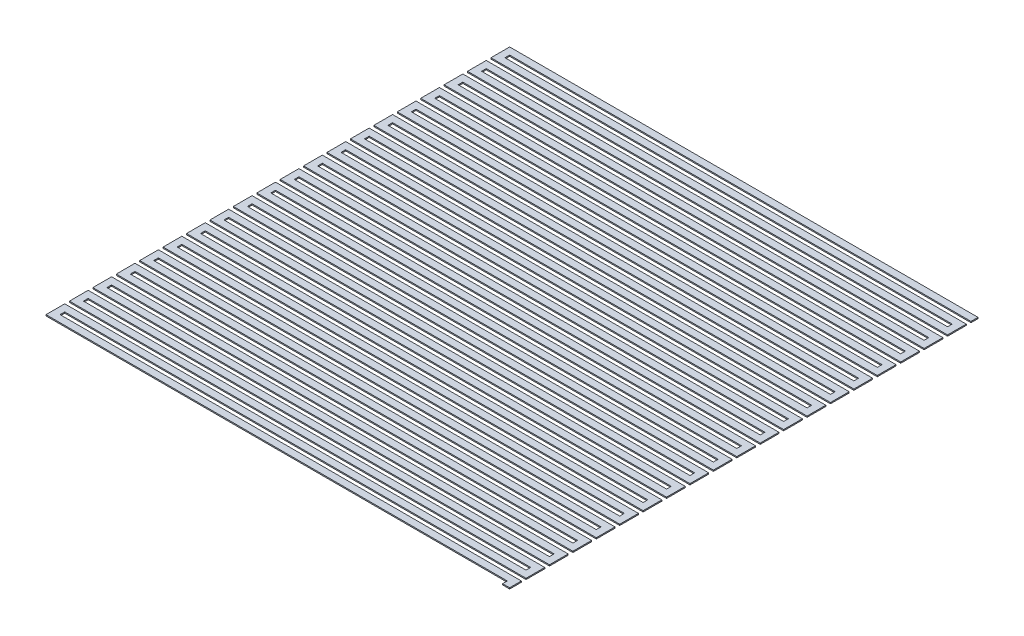
SolidWorks part; units mm, degrees
ref_plane "Front Plane" through (0, 0, 0) normal (0, 0, 1) x (1, 0, 0)
ref_plane "Top Plane" through (0, 0, 0) normal (0, 1, 0) x (1, 0, 0)
ref_plane "Right Plane" through (0, 0, 0) normal (1, 0, 0) x (0, 0, -1)
sketch "Base Guidlines" plane through (0, 0, 0) normal (0, 1, 0) x (1, 0, 0)
  line L0 (-4.5961, 9.2) -> (-4.5961, 8.5)
  line L1 (-10, -10) -> (10, -10)
  line L2 (-10, -10) -> (-10, 10)
  line L3 (-10, 10) -> (10, 10)
  line L4 (10, -10) -> (10, 10)
  line L5 (-10, -10) -> (10, 10) construction
  line L6 (-10, 10) -> (10, -10) construction
  line L7 (-10, 10) -> (10, 10)
  line L8 (-10, 10) -> (-10, 9.2)
  line L9 (-10, 9.2) -> (10, 9.2)
  line L10 (10, 10) -> (10, 9.2)
  line L11 (-4.5961, -9.2) -> (-4.5961, -8.5)
  line L12 (-10, -10) -> (10, -10)
  line L13 (-10, -10) -> (-10, -9.2)
  line L14 (-10, -9.2) -> (10, -9.2)
  line L15 (10, -10) -> (10, -9.2)
  line L17 (-10, -9.2) -> (10, -9.2)
  line L18 (-10, -9.2) -> (-10, -8.5)
  line L19 (-10, -8.5) -> (10, -8.5)
  line L20 (10, -9.2) -> (10, -8.5)
  line L21 (-10, 9.2) -> (10, 9.2)
  line L22 (-10, 9.2) -> (-10, 8.5)
  line L23 (-10, 8.5) -> (10, 8.5)
  line L24 (10, 9.2) -> (10, 8.5)
  point P0 (0, 0)
  dimension "D1" = 20
  dimension "D2" = 20
  dimension "D3" = 0.7
  dimension "D4" = 0.7
sketch "Mirror axis x" plane through (0, 0, 0) normal (0, 1, 0) x (1, 0, 0)
  line L0 (-10, 0) -> (10, 0)
  line L1 (-10, -10) -> (-10, 10) construction
  line L2 (10, -10) -> (10, 10) construction
sketch "TopBlock" plane through (0, 0, 0) normal (0, 1, 0) x (1, 0, 0)
  line L0 (-10, 10) -> (10, -10) construction
  line L1 (-10, 10) -> (-9.7, 10)
  line L2 (-10, 10) -> (-10, 9.7)
  line L3 (10, 9.2) -> (10, 9.5)
  line L4 (-9.7, 10) -> (10, 10)
  line L5 (-9.7, 9.7) -> (-9.7, 9.5)
  line L6 (-10, 9.2) -> (-9.7, 9.2)
  line L7 (-10, 9.2) -> (-10, 9.5)
  line L8 (-9.7, 9.5) -> (9.7, 9.5)
  line L10 (-10, 9.7) -> (-10, 9.5)
  line L11 (-9.7, 9.7) -> (10, 9.7)
  line L12 (10, 9.7) -> (10, 10)
  line L13 (10, -10) -> (10, 10) construction
  line L14 (10, 9.2) -> (9.7, 9.2)
  line L15 (10, 9.5) -> (9.7, 9.5)
  line L24 (9.7, 9.2) -> (-9.7, 9.2)
  dimension "D1" = 0.3
  dimension "D2" = 0.3
extrude "Extruded object" add sketch "TopBlock" along normal blind 0.05
sketch "Mirror axis y" plane through (0, 0, 0) normal (0, 1, 0) x (1, 0, 0)
  line L0 (0, 10) -> (0, -10)
  line L3 (10, 10) -> (-10, 10) construction
  dimension "D1" = 20
sketch "GapandInbetween" plane through (0, 0, 0) normal (0, 1, 0) x (1, 0, 0)
  line L0 (10, 9.2) -> (10, 9)
  line L1 (10, -10) -> (10, 10) construction
  line L2 (10, 9) -> (10, 8.7)
  line L3 (-9.7, 8.5) -> (-9.7, 8.7)
  line L4 (9.7, 9) -> (9.7, 9.2)
  line L5 (-10, 9.2) -> (10, 9.2) construction
  line L6 (9.7, 9.2) -> (10, 9.2)
  line L7 (10, 8.7) -> (-9.7, 8.7)
  line L8 (-10, -10) -> (-10, 10) construction
  line L9 (9.7, 9) -> (-10, 9)
  line L10 (-10, 9) -> (-10, 8.7)
  line L11 (-10, 8.7) -> (-10, 8.5)
  line L12 (-9.7, 8.5) -> (10, 8.5)
  line L13 (-10, 8.5) -> (10, 8.5) construction
  line L14 (-10, 8.5) -> (-10, 8.2)
  line L15 (-10, 8.2) -> (9.7, 8.2)
  line L16 (9.7, 8.2) -> (10, 8.2)
  line L17 (10, 8.2) -> (10, 8.5)
  dimension "D1" = 0.2
  dimension "D2" = 0.3
  dimension "D3" = 0.3
  dimension "D4" = 0.3
  dimension "D5" = 0.3
extrude "Boss-Extrude2" add sketch "GapandInbetween" along normal blind 0.05
pattern_linear "LPattern1" count 19 spacing 1 along (0, 0, 1) of "Boss-Extrude2"
sketch "Sketch1" plane through (0, 0, 0) normal (0, 1, 0) x (1, 0, 0)
  line L1 (10, -9.8) -> (10, -10)
  line L2 (9.7, -9.8) -> (9.7, -10)
  line L3 (9.7, -10) -> (10, -10)
  line L4 (10, -9.8) -> (9.7, -9.8)
  line L5 (-10, -9.8) -> (10, -9.8) construction
  dimension "D1" = 0.2
extrude "Boss-Extrude3" add sketch "Sketch1" along normal blind 0.05
